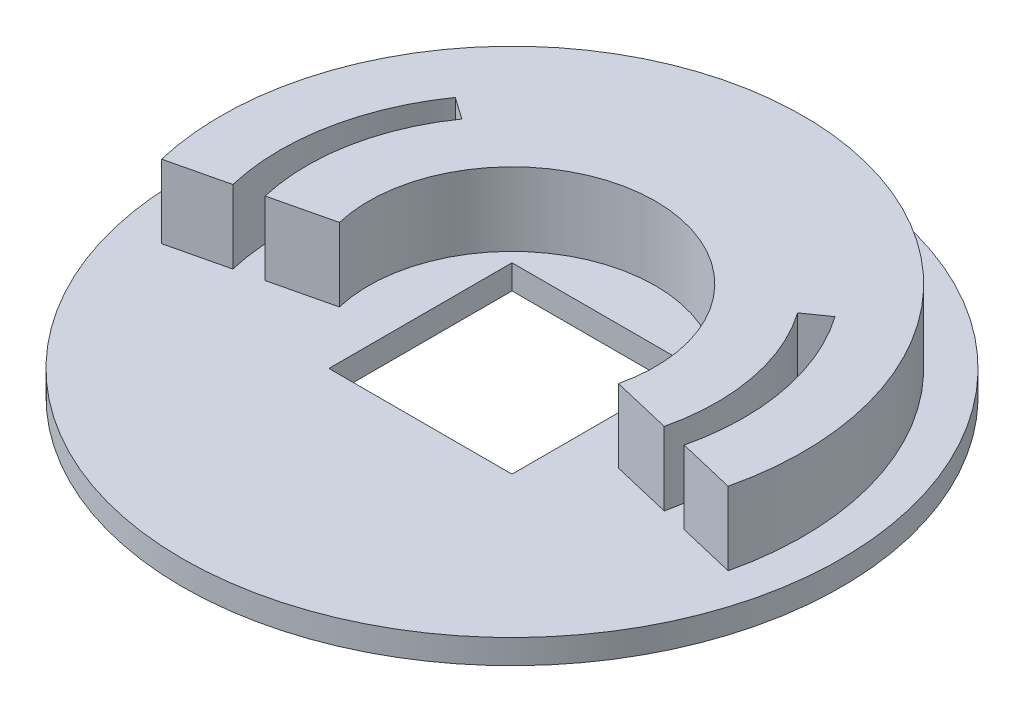
SolidWorks part; units mm, degrees
ref_plane "Front Plane" through (0, 0, 0) normal (0, 0, 1) x (1, 0, 0)
ref_plane "Top Plane" through (0, 0, 0) normal (0, 1, 0) x (1, 0, 0)
ref_plane "Right Plane" through (0, 0, 0) normal (1, 0, 0) x (0, 0, -1)
sketch "Sketch1" plane through (0, 0, 0) normal (0, 1, 0) x (1, 0, 0)
  line L0 (-55, 0) -> (55, 0) construction
  line L1 (-23.2072, -5.5) -> (-28.6416, 17.4303) construction
  line L2 (-23.2072, -5.5) -> (-11.4333, -2.7096)
  line L3 (0, -55) -> (0, 55) construction
  line L4 (23.2072, -5.5) -> (11.4333, -2.7096)
  circle A0 centre (0, 0) radius 11.75 construction
  circle A1 centre (0, 0) radius 23.85 construction
  arc A2 (-23.2072, -5.5) -> (23.2072, -5.5) centre (0, 0) cw
  arc A3 (-11.4333, -2.7096) -> (11.4333, -2.7096) centre (0, 0) cw
  point P15 (-11.4984, -2.4186)
  dimension "D1" = 23.5
  dimension "D2" = 47.7
  dimension "D3" = 5.5
extrude "Boss-Extrude1" add sketch "Sketch1" along normal blind 6 contours A2 L4 A3 L2
sketch "Sketch2" plane through (0, 0, 0) normal (0, -1, 0) x (1, 0, 0)
  line L5 (-7.5, -7.5) -> (7.5, 7.5) construction
  line L6 (7.5, -7.5) -> (-7.5, 7.5) construction
  line L18 (-7.5, 7.5) -> (7.5, 7.5)
  line L19 (-7.5, 7.5) -> (-7.5, -7.5)
  line L20 (-7.5, -7.5) -> (7.5, -7.5)
  line L22 (7.5, 7.5) -> (7.5, -7.5)
  circle A1 centre (0, 0) radius 27
  point P1 (0, 0)
  dimension "D1" = 54
  dimension "D2" = 15
extrude "Boss-Extrude2" add sketch "Sketch2" along normal blind 2
sketch "Sketch3" plane through (0, 6, 0) normal (0, 1, 0) x (1, 0, 0)
  line L0 (-23.2072, -5.5) -> (-11.4333, -2.7096) construction
  line L1 (-23.2072, -5.5) -> (-11.4333, -2.7096) construction
  line L2 (-15.5555, 10.9099) -> (-13.7543, 9.6467)
  line L3 (-18.4879, -4.3816) -> (-16.3472, -3.8742)
  circle A0 centre (0, 0) radius 17.8 construction
  arc A1 (-18.4879, -4.3816) -> (-15.5555, 10.9099) centre (0, 0) cw
  arc A2 (-16.3472, -3.8742) -> (-13.7543, 9.6467) centre (0, 0) cw
  point P3 (5.2042, -17.0222)
  point P6 (-17.3202, -4.1048)
  dimension "D1" = 1.2
  dimension "D2" = 2.2
extrude "Cut-Extrude1" cut sketch "Sketch3" against normal up to surface (6 mm away) up to face at (0, 0, 0)
mirror "Mirror1" about plane through (0, 0, 0) normal (1, 0, 0) of "Cut-Extrude1"
